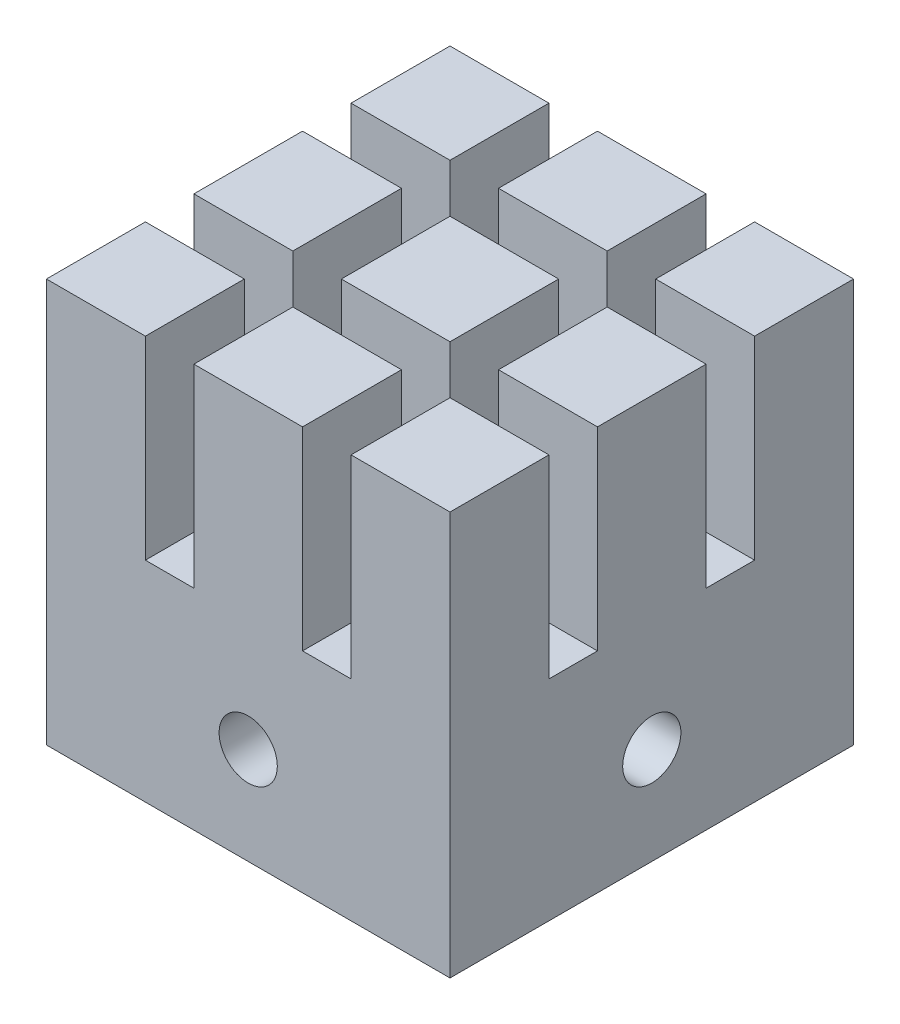
SolidWorks part; units mm, degrees
ref_plane "Front Plane" through (0, 0, 0) normal (0, 0, 1) x (1, 0, 0)
ref_plane "Top Plane" through (0, 0, 0) normal (0, 1, 0) x (1, 0, 0)
ref_plane "Right Plane" through (0, 0, 0) normal (1, 0, 0) x (0, 0, -1)
ref_plane "Plane1" through (0, 0, -16.256) normal (0, 0, 1) x (1, 0, 0)
sketch "Sketch2" plane through (0, 0, 0) normal (0, 0, 1) x (1, 0, 0)
  line L1 (-8.128, 12.7) -> (18.288, 12.7)
  line L2 (-8.128, 12.7) -> (-8.128, -13.716)
  line L3 (-8.128, -13.716) -> (18.288, -13.716)
  line L4 (18.288, 12.7) -> (18.288, -13.716)
  dimension "D1" = 26.416
  dimension "D2" = 26.416
  dimension "D3" = 8.128
  dimension "D4" = 12.7
extrude "Boss-Extrude1" add sketch "Sketch2" against normal blind 26.416
ref_plane "Plane2" through (0, 0, -8.128) normal (0, 0, 1) x (1, 0, 0)
sketch "Sketch4" plane through (0, 12.7, 0) normal (0, 1, 0) x (1, 0, 0)
  line L0 (-8.128, 26.416) -> (-8.128, 0) construction
  line L1 (-1.651, 26.416) -> (1.524, 26.416)
  line L2 (-1.651, 26.416) -> (-1.651, 0)
  line L3 (-1.651, 0) -> (1.524, 0)
  line L4 (1.524, 26.416) -> (1.524, 0)
  line L5 (8.636, 26.416) -> (11.811, 26.416)
  line L6 (8.636, 26.416) -> (8.636, 0)
  line L7 (8.636, 0) -> (11.811, 0)
  line L8 (11.811, 26.416) -> (11.811, 0)
  line L9 (18.288, 19.939) -> (-8.128, 19.939)
  line L10 (18.288, 19.939) -> (18.288, 16.764)
  line L11 (18.288, 16.764) -> (-8.128, 16.764)
  line L12 (-8.128, 19.939) -> (-8.128, 16.764)
  line L13 (-8.128, 9.652) -> (18.288, 9.652)
  line L14 (-8.128, 9.652) -> (-8.128, 6.477)
  line L15 (-8.128, 6.477) -> (18.288, 6.477)
  line L16 (18.288, 9.652) -> (18.288, 6.477)
  line L17 (18.288, 26.416) -> (18.288, 0) construction
  line L18 (18.288, 26.416) -> (-8.128, 26.416) construction
  line L19 (18.288, 0) -> (-8.128, 0) construction
  dimension "D1" = 3.175
  dimension "D2" = 9.652
  dimension "D3" = 7.112
  dimension "D4" = 7.112
  dimension "D5" = 9.652
extrude "Cut-Extrude3" cut sketch "Sketch4" against normal blind 12.7 contours L2 L3 L4 L1 | L13 L16 L15 L14 | L9 L12 L11 L10 | L6 L7 L8 L5
sketch "Sketch7" plane through (0, 0, 0) normal (0, 0, 1) x (1, 0, 0)
  line L0 (-8.128, -13.716) -> (18.288, -13.716) construction
  line L1 (18.288, -13.716) -> (18.288, 12.7) construction
  circle A0 centre (5.08, -7.366) radius 1.905
  dimension "D3" = 3.81
  dimension "D1" = 6.35
  dimension "D2" = 13.208
extrude "Cut-Extrude5" cut sketch "Sketch7" against normal through all
sketch "Sketch8" plane through (18.288, 0, 0) normal (1, 0, 0) x (0, 0, -1)
  line L0 (0, -13.716) -> (0, 12.7) construction
  line L1 (26.416, -13.716) -> (0, -13.716) construction
  circle A0 centre (13.208, -7.366) radius 1.905
  dimension "D3" = 3.81
  dimension "D1" = 13.208
  dimension "D2" = 6.35
extrude "Cut-Extrude6" cut sketch "Sketch8" against normal through all
